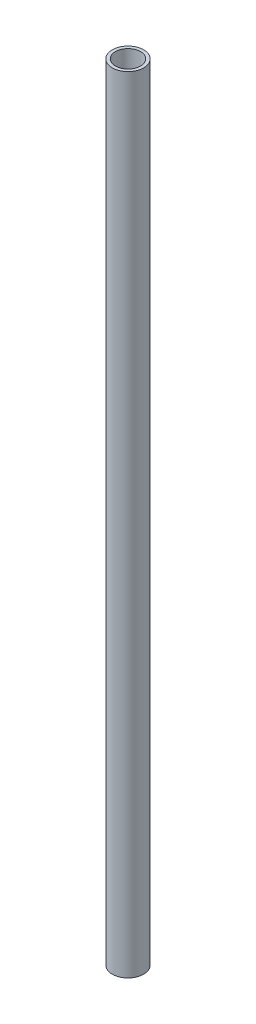
SolidWorks part; units mm, degrees
ref_plane "前视基准面" through (0, 0, 0) normal (0, 0, 1) x (1, 0, 0)
ref_plane "上视基准面" through (0, 0, 0) normal (0, 1, 0) x (1, 0, 0)
ref_plane "右视基准面" through (0, 0, 0) normal (1, 0, 0) x (0, 0, -1)
sketch "草图1" plane through (0, 0, 0) normal (0, 1, 0) x (1, 0, 0)
  circle A0 centre (0, 0) radius 10
  circle A1 centre (0, 0) radius 8
  dimension "D1" = 20
  dimension "D2" = 2
extrude "凸台-拉伸1" add sketch "草图1" along normal blind 500
